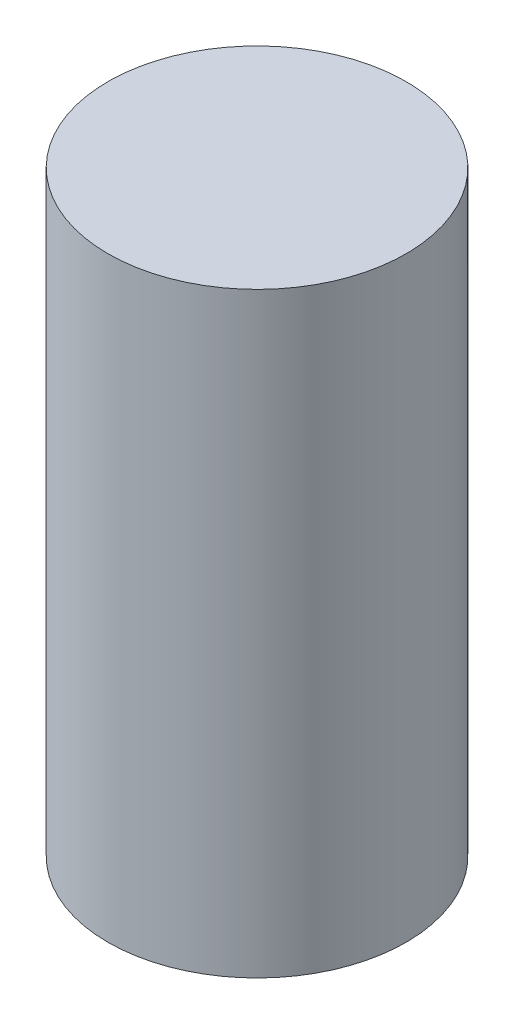
SolidWorks part; units mm, degrees
ref_plane "Front Plane" through (0, 0, 0) normal (0, 0, 1) x (1, 0, 0)
ref_plane "Top Plane" through (0, 0, 0) normal (0, 1, 0) x (1, 0, 0)
ref_plane "Right Plane" through (0, 0, 0) normal (1, 0, 0) x (0, 0, -1)
sketch "Sketch1" plane through (0, 0, 0) normal (0, 1, 0) x (1, 0, 0)
  circle A0 centre (0, 0) radius 3.5
  dimension "D1" = 7
extrude "Boss-Extrude1" add sketch "Sketch1" along normal blind 14
